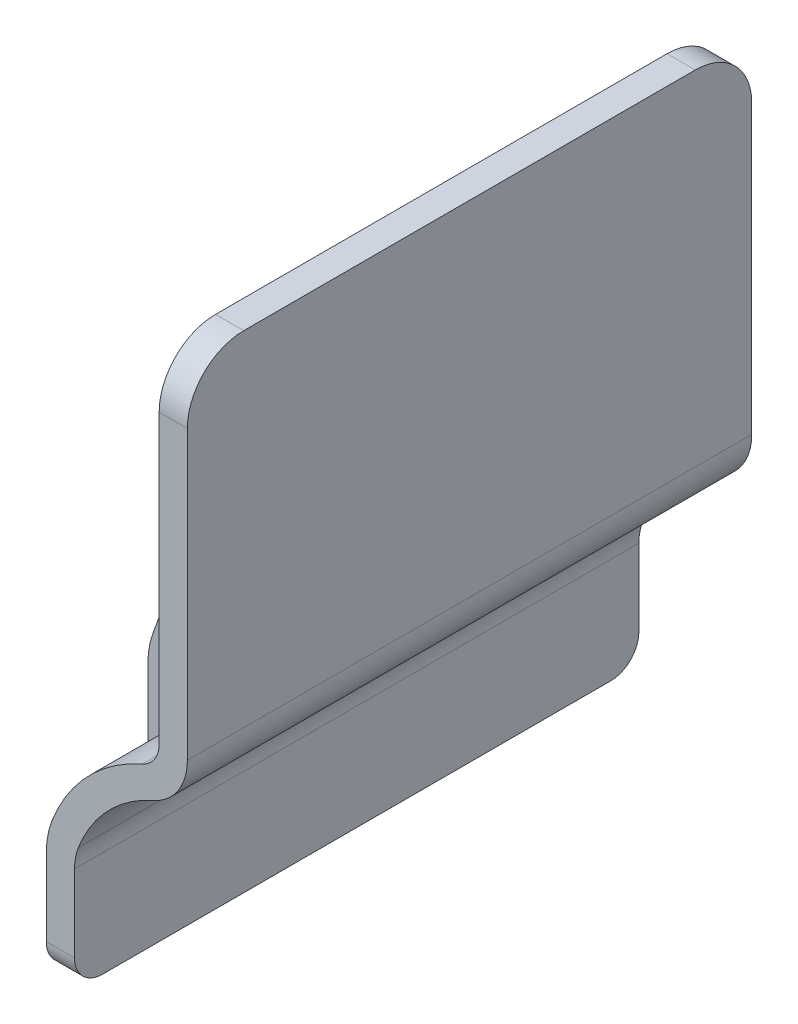
SolidWorks part; units mm, degrees
ref_plane "Front Plane" through (0, 0, 0) normal (0, 0, 1) x (1, 0, 0)
ref_plane "Top Plane" through (0, 0, 0) normal (0, 1, 0) x (1, 0, 0)
ref_plane "Right Plane" through (0, 0, 0) normal (1, 0, 0) x (0, 0, -1)
ref_plane "Plane1" through (0, 0, -83) normal (0, 0, 1) x (1, 0, 0)
sketch "Sketch2" plane through (0, 0, -83) normal (0, 0, 1) x (1, 0, 0)
  line L1 (-4, 165.6352) -> (-4, 147)
  line L3 (16, 253.25) -> (16, 192.328)
  line L5 (11, 253.25) -> (11, 192.328)
  line L6 (-9, 165.6352) -> (-9, 147)
  line L7 (11, 253.25) -> (16, 253.25)
  line L8 (-9, 147) -> (-4, 147)
  arc A1 (-4, 165.6352) -> (-3.3333, 169.2253) centre (6, 165.6352) cw
  arc A2 (8, 187.7455) -> (11, 192.328) centre (6, 192.328) ccw
  arc A3 (10, 183.1629) -> (-3.3333, 169.2253) centre (20, 160.25) ccw
  arc A4 (10, 183.1629) -> (16, 192.328) centre (6, 192.328) ccw
  arc A5 (8, 187.7455) -> (-8, 171.0203) centre (20, 160.25) ccw
  arc A6 (-9, 165.6352) -> (-8, 171.0203) centre (6, 165.6352) cw
  dimension "D1" = 5
extrude "Boss-Extrude1" add sketch "Sketch2" along normal mid plane 100
fillet "Fillet1" radius 10 2 edges at (13.5, 253.25, -33) (13.5, 253.25, -133)
fillet "Fillet2" radius 5 2 edges at (-6.5, 147, -33) (-6.5, 147, -133)
ref_plane "Plane2" through (0, 0, -83) normal (0, 0, 1) x (1, 0, 0)
ref_plane "Plane3" through (0, 0, -53) normal (0, 0, 1) x (1, 0, 0)
sketch "Sketch4" plane through (0, 0, -53) normal (0, 0, 1) x (1, 0, 0)
  line L6 (10.0954, 240.7646) -> (-8.0954, 190.7858)
  line L7 (-9, 185.6555) -> (-9, 165.6352)
  line L8 (11, 192.328) -> (11, 245.8949)
  arc A10 (-8.0954, 190.7858) -> (-9, 185.6555) centre (6, 185.6555) ccw
  arc A11 (-8, 171.0203) -> (-9, 165.6352) centre (6, 165.6352) ccw
  arc A12 (8, 187.7455) -> (-8, 171.0203) centre (20, 160.25) ccw
  arc A13 (8, 187.7455) -> (11, 192.328) centre (6, 192.328) ccw
  arc A14 (10.0954, 240.7646) -> (11, 245.8949) centre (-4, 245.8949) ccw
extrude "Boss-Extrude3" add sketch "Sketch4" against normal mid plane 4
ref_plane "Plane4" through (0, 0, -113) normal (0, 0, -1) x (-1, 0, 0)
sketch "Sketch5" plane through (0, 0, -113) normal (0, 0, -1) x (-1, 0, 0)
  line L3 (-11, 245.8949) -> (-11, 192.328)
  line L4 (9, 165.6352) -> (9, 185.6555)
  line L5 (8.0954, 190.7858) -> (-10.0954, 240.7646)
  line L6 (-11, 245.8949) -> (-11, 192.328)
  line L7 (9, 165.6352) -> (9, 185.6555)
  line L8 (8.0954, 190.7858) -> (-10.0954, 240.7646)
  arc A5 (-11, 245.8949) -> (-10.0954, 240.7646) centre (4, 245.8949) ccw
  arc A6 (-11, 192.328) -> (-8, 187.7455) centre (-6, 192.328) ccw
  arc A7 (8, 171.0203) -> (-8, 187.7455) centre (-20, 160.25) ccw
  arc A8 (9, 165.6352) -> (8, 171.0203) centre (-6, 165.6352) ccw
  arc A9 (9, 185.6555) -> (8.0954, 190.7858) centre (-6, 185.6555) ccw
  arc A10 (-11, 245.8949) -> (-10.0954, 240.7646) centre (4, 245.8949) ccw
  arc A11 (-11, 192.328) -> (-8, 187.7455) centre (-6, 192.328) ccw
  arc A12 (8, 171.0203) -> (-8, 187.7455) centre (-20, 160.25) ccw
  arc A13 (9, 165.6352) -> (8, 171.0203) centre (-6, 165.6352) ccw
  arc A14 (9, 185.6555) -> (8.0954, 190.7858) centre (-6, 185.6555) ccw
  dimension "D1" = 0
extrude "Boss-Extrude4" add sketch "Sketch5" along normal mid plane 4
